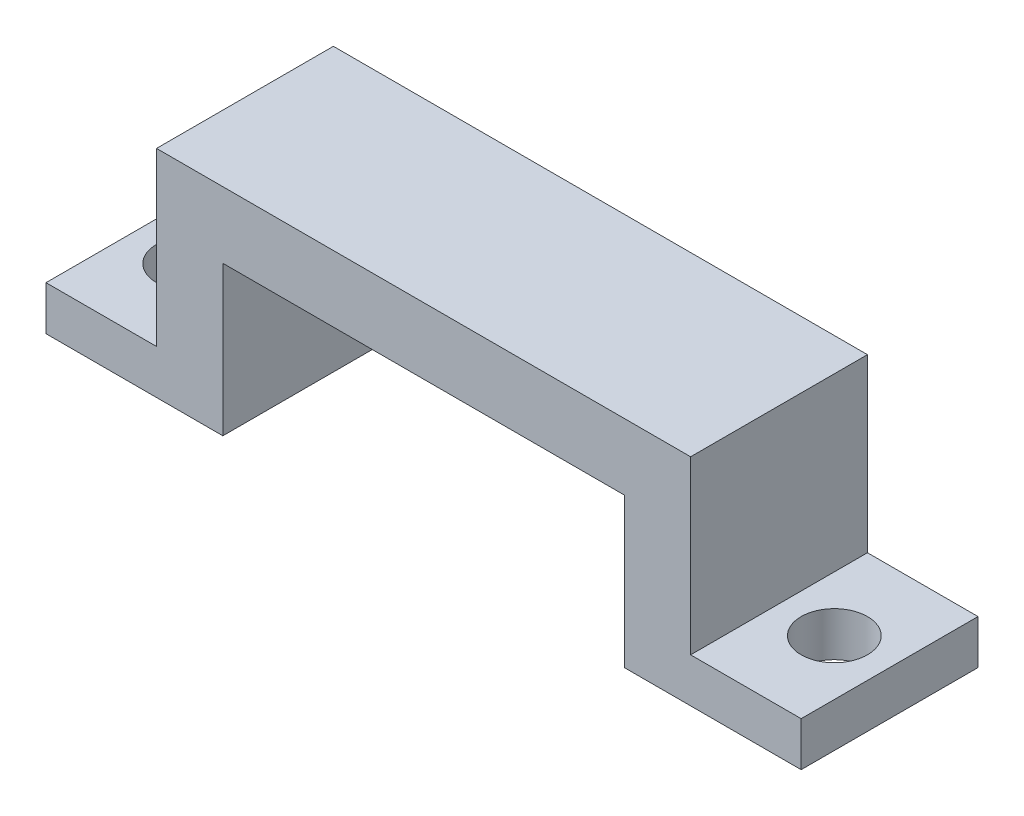
SolidWorks part; units mm, degrees
ref_plane "Front Plane" through (0, 0, 0) normal (0, 0, 1) x (1, 0, 0)
ref_plane "Top Plane" through (0, 0, 0) normal (0, 1, 0) x (1, 0, 0)
ref_plane "Right Plane" through (0, 0, 0) normal (1, 0, 0) x (0, 0, -1)
sketch "Sketch2" plane through (0, 0, 0) normal (0, 0, 1) x (1, 0, 0)
  line L1 (-9.23, -3.38) -> (8.93, -3.38)
  line L2 (-9.23, -3.38) -> (-9.23, 3.38)
  line L3 (-9.23, 3.38) -> (8.93, 3.38)
  line L4 (8.93, -3.38) -> (8.93, 3.38)
  line L5 (11.93, -1.38) -> (11.93, 6.38)
  line L6 (-12.23, 6.38) -> (11.93, 6.38)
  line L7 (-12.23, -1.38) -> (-12.23, 6.38)
  line L8 (-9.23, -3.38) -> (-12.23, -3.38)
  line L9 (8.93, -3.38) -> (11.93, -3.38)
  line L10 (-12.23, -6.38) -> (-12.23, 6.38) construction
  line L11 (-12.23, -6.38) -> (11.93, -6.38) construction
  line L12 (11.93, -6.38) -> (11.93, 6.38) construction
  line L14 (-12.23, -3.38) -> (-17.23, -3.38)
  line L16 (-12.23, -1.38) -> (-17.23, -1.38)
  line L17 (-17.23, -3.38) -> (-17.23, -1.38)
  line L18 (11.93, -3.38) -> (16.93, -3.38)
  line L20 (11.93, -1.38) -> (16.93, -1.38)
  line L21 (16.93, -3.38) -> (16.93, -1.38)
  point P0 (0, 0)
  dimension "D1" = 18.16
  dimension "D2" = 6.76
  dimension "D4" = 2
  dimension "D5" = 5
  dimension "D6" = 2
  dimension "D7" = 5
  dimension "D3" = 3
extrude "Boss-Extrude1" add sketch "Sketch2" along normal blind 8 contours L18 L21 L20 L5 L6 L7 L16 L17 L14 L8 L2 L3 L4 L9
sketch "Sketch3" plane through (0, -1.38, 0) normal (0, 1, 0) x (1, 0, 0)
  line L0 (11.93, 0) -> (16.93, 0) construction
  line L1 (11.93, -8) -> (11.93, 0) construction
  line L2 (-12.23, 0) -> (-17.23, 0) construction
  line L3 (-12.23, -8) -> (-12.23, 0) construction
  circle A0 centre (14.43, -4) radius 1.9118
  circle A1 centre (-14.73, -4) radius 1.7839
  dimension "D1" = 4
  dimension "D2" = 2.5
  dimension "D3" = 4
  dimension "D4" = 2.5
hole_wizard "Ø3.0 (3) Diameter Hole1" positions "Sketch4" profile "Sketch6" hole size "Ø3.0" standard "ANSI Metric" end condition through all
sketch "Sketch4" plane through (0, -1.38, 0) normal (0, 1, 0) x (1, 0, 0)
  point P0 (14.43, -4)
  point P4 (-14.73, -4)
sketch "Sketch6" plane through (14.43, -1.38, 4) normal (1, 0, 0) x (0, 0, 1)
  line L0 (0, 0) -> (0, 2)
  line L1 (0, 2) -> (1.5, 2)
  line L2 (1.5, 2) -> (1.5, 0)
  line L5 (1.5, 0) -> (0, 0)
  line L11 (0, -6.35) -> (0, 107.95) construction
  dimension "Thru Hole Dia." = 3
  dimension "Thru Hole Depth" = 2
